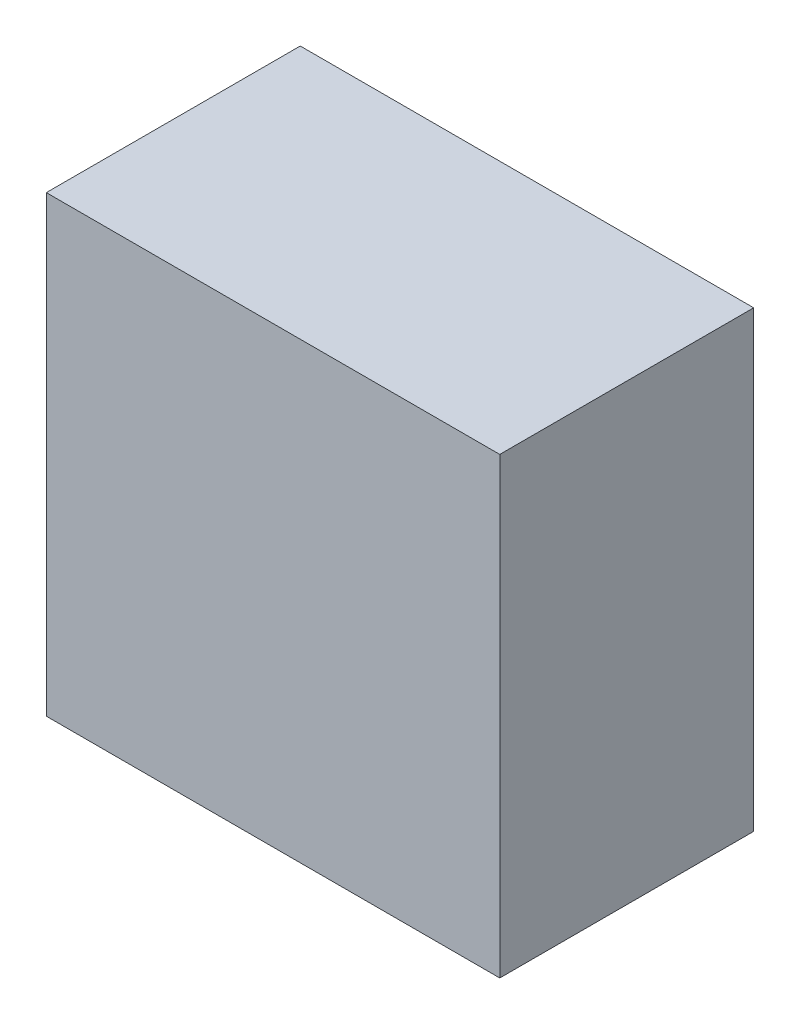
SolidWorks part; units mm, degrees
ref_plane "Front Plane" through (0, 0, 0) normal (0, 0, 1) x (1, 0, 0)
ref_plane "Top Plane" through (0, 0, 0) normal (0, 1, 0) x (1, 0, 0)
ref_plane "Right Plane" through (0, 0, 0) normal (1, 0, 0) x (0, 0, -1)
sketch "Sketch1" plane through (0, 0, 0) normal (0, 0, 1) x (1, 0, 0)
  line L1 (-62.5, 62.5) -> (62.5, 62.5)
  line L2 (-62.5, 62.5) -> (-62.5, -62.5)
  line L3 (-62.5, -62.5) -> (62.5, -62.5)
  line L4 (62.5, 62.5) -> (62.5, -62.5)
  line L5 (-62.5, 62.5) -> (62.5, -62.5) construction
  line L6 (-62.5, -62.5) -> (62.5, 62.5) construction
  point P0 (0, 0)
  dimension "D1" = 125
extrude "Boss-Extrude1" add sketch "Sketch1" along normal mid plane 70
